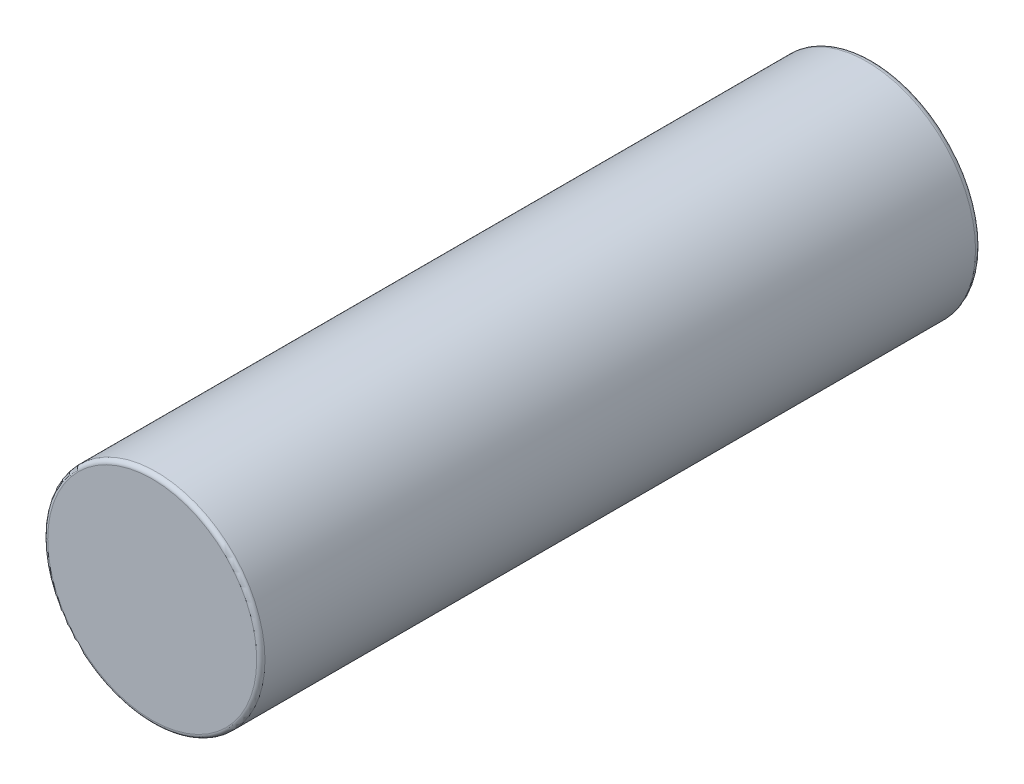
SolidWorks part; units mm, degrees
ref_plane "Front Plane" through (0, 0, 0) normal (0, 0, 1) x (1, 0, 0)
ref_plane "Top Plane" through (0, 0, 0) normal (0, 1, 0) x (1, 0, 0)
ref_plane "Right Plane" through (0, 0, 0) normal (1, 0, 0) x (0, 0, -1)
sketch "Sketch1" plane through (0, 0, 0) normal (0, 1, 0) x (1, 0, 0)
  line L0 (0, 0) -> (0, 70.09) construction
  line L1 (0, 70.09) -> (4.3922, 70.09)
  line L2 (4.5593, 69.9999) -> (5.4407, 68.6601)
  line L3 (5.6078, 68.57) -> (8.1, 68.57) construction
  line L4 (8.1, 68.57) -> (8.1, 69.27) construction
  line L6 (10.52, 69.21) -> (10.52, 0.4)
  line L7 (10.12, 0) -> (0, 0)
  line L8 (8.1, 69.156) -> (8.1, 68.97)
  line L9 (8.1, 68.97) -> (7.745, 68.97)
  line L10 (7.745, 68.97) -> (7.745, 68.57) construction
  line L11 (7.745, 68.97) -> (7.745, 68.67)
  line L12 (7.745, 68.67) -> (6.955, 68.67)
  line L13 (6.955, 68.67) -> (6.955, 68.57)
  line L14 (0, 69.79) -> (4.3383, 69.79)
  line L15 (4.3383, 69.79) -> (5.3383, 68.27)
  line L16 (6.955, 68.57) -> (5.6078, 68.57)
  line L17 (0, 70.09) -> (0, 69.79)
  line L18 (4.3383, 69.79) -> (5.1901, 68.4952) construction
  line L19 (5.3383, 68.27) -> (0, 68.27)
  line L20 (0, 68.27) -> (0, 0)
  arc A1 (9.94, 69.79) -> (10.52, 69.21) centre (9.94, 69.21) cw
  arc A2 (9.94, 69.79) -> (8.2011, 69.3298) centre (9.94, 66.2746) ccw
  arc A3 (5.4407, 68.6601) -> (5.6078, 68.57) centre (5.6078, 68.77) ccw
  arc A4 (4.3922, 70.09) -> (4.5593, 69.9999) centre (4.3922, 69.89) cw
  arc A5 (8.1, 69.156) -> (8.2011, 69.3298) centre (8.3, 69.156) cw
  arc A6 (4.3383, 69.79) -> (4.3383, 69.79) centre (4.3383, 69.79) cw
  arc A7 (10.52, 0.4) -> (10.12, 0) centre (10.12, 0.4) cw
  point P14 (5.5, 68.57)
  point P17 (4.5, 70.09)
  dimension "D10" = 0.58
  dimension "D11" = 0.2
  dimension "D14" = 0.2
  dimension "D18" = 0.3
  dimension "D19" = 0.4
  dimension "D1" = 21.04
  dimension "D2" = 70.09
  dimension "D3" = 9
  dimension "D4" = 11
  dimension "D5" = 0.3
  dimension "D6" = 0.58
  dimension "D7" = 2.42
  dimension "D8" = 1.22
  dimension "D9" = 0.7
  dimension "D12" = 0.3
  dimension "D13" = 7.745
  dimension "D15" = 13.91
  dimension "D16" = 0.2
  dimension "D17" = 0.3
revolve "Revolve1" add sketch "Sketch1" angle 360 about L0
sketch "Sketch2" plane through (0, 0, -70.09) normal (0, 0, -1) x (-1, 0, 0)
  line L0 (-1.65, 4.809) -> (1.65, 4.809) construction
  arc A2 (2.1512, 4.5732) -> (5.0361, -0.4236) centre (0, 0) cw construction
  arc A3 (5.5881, -0.47) -> (2.387, 5.0744) centre (0, 0) ccw
  arc A4 (4.4842, -0.3772) -> (1.9155, 4.072) centre (0, 0) ccw
  arc A5 (4.4842, -0.3772) -> (5.5881, -0.47) centre (5.0361, -0.4236) ccw
  arc A6 (2.387, 5.0744) -> (1.9155, 4.072) centre (2.1512, 4.5732) ccw
  circle A7 centre (0, 0) radius 4.5 construction
  arc A8 (2.8849, -4.1496) -> (-2.8849, -4.1496) centre (0, 0) cw construction
  arc A9 (-3.2011, -4.6044) -> (3.2011, -4.6044) centre (0, 0) ccw
  arc A10 (-2.5687, -3.6948) -> (2.5687, -3.6948) centre (0, 0) ccw
  arc A11 (-2.5687, -3.6948) -> (-3.2011, -4.6044) centre (-2.8849, -4.1496) ccw
  arc A12 (3.2011, -4.6044) -> (2.5687, -3.6948) centre (2.8849, -4.1496) ccw
  arc A13 (-5.0361, -0.4236) -> (-2.1512, 4.5732) centre (0, 0) cw construction
  arc A14 (-2.387, 5.0744) -> (-5.5881, -0.47) centre (0, 0) ccw
  arc A15 (-1.9155, 4.072) -> (-4.4842, -0.3772) centre (0, 0) ccw
  arc A16 (-1.9155, 4.072) -> (-2.387, 5.0744) centre (-2.1512, 4.5732) ccw
  arc A17 (-5.5881, -0.47) -> (-4.4842, -0.3772) centre (-5.0361, -0.4236) ccw
  circle A19 centre (0, 0) radius 5.6078 construction
  point P5 (4.3768, 2.527)
  point P12 (1.65, 4.809)
  point P13 (-1.65, 4.809)
  point P16 (0, -5.0539)
  point P23 (-4.3768, 2.527)
  point P28 (0, 0)
  dimension "D2" = 3.3
  dimension "D1" = 3
extrude "Cut-Extrude1" cut sketch "Sketch2" against normal up to surface (1.82 mm away) up to face at (5.3383, 0, -68.27)
sketch "Sketch3" [suppressed] plane through (0, 0, 0) normal (0, 0, 1) x (1, 0, 0)
  circle A0 centre (0, 0) radius 5.285
  circle A1 centre (0, 0) radius 5.54
  dimension "D1" = 10.57
  dimension "D2" = 11.08
extrude "Cut-Extrude2" [suppressed] cut sketch "Sketch3" against normal blind 0.28
ref_plane "Plane1" [suppressed] through (-10.52, 0, 0) normal (-1, 0, 0) x (0, 0, 1)
sketch "Sketch4" [suppressed] plane through (-10.52, 0, 0) normal (-1, 0, 0) x (0, 0, 1)
  line L0 (-16.87, 0) -> (-46.4484, 0) construction
  line L3 (-70.0584, 4.072) -> (-70.0584, -0.3772) construction
  text T0 "LGDBM502170\r\n" font "SWIsop1" height 3.5
  dimension "D1" = 23.61
  dimension "D2" = 16.87
extrude "Cut-Extrude3" [suppressed] cut sketch "Sketch4" against normal offset from surface (0.5217 mm away) 0.001
ref_plane "Plane2" through (0, 0, -35.045) normal (0, 0, -1) x (-1, 0, 0)
